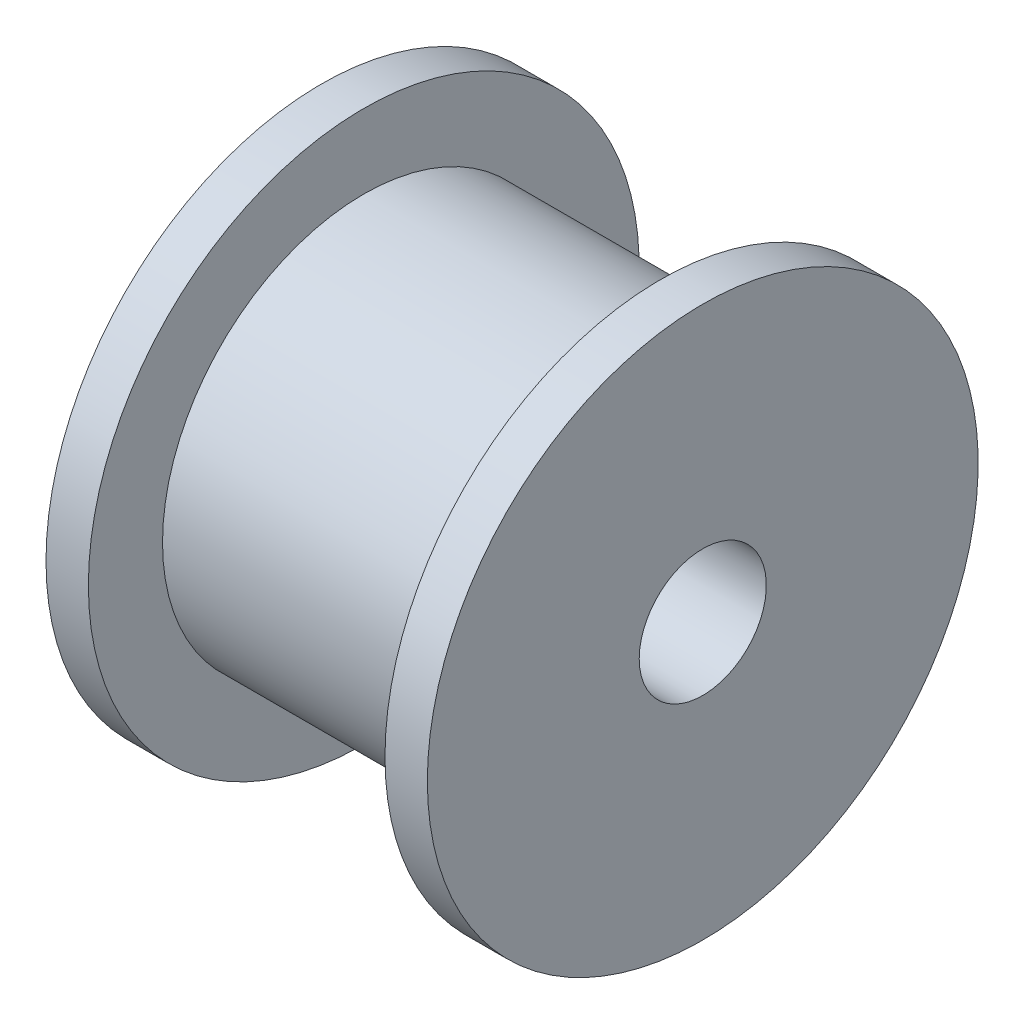
SolidWorks part; units mm, degrees
ref_plane "Спереди" through (0, 0, 0) normal (0, 0, 1) x (1, 0, 0)
ref_plane "Сверху" through (0, 0, 0) normal (0, 1, 0) x (1, 0, 0)
ref_plane "Справа" through (0, 0, 0) normal (1, 0, 0) x (0, 0, -1)
sketch "Эскиз1" plane through (0, 0, 0) normal (0, 0, 1) x (1, 0, 0)
  line L0 (0, 12.4245) -> (0, -12.3679) construction
  line L1 (-12.283, 0) -> (12.4528, 0) construction
  line L2 (0, 4.75) -> (3.5, 4.75)
  line L3 (3.5, 4.75) -> (3.5, 6.5)
  line L4 (3.5, 6.5) -> (4.5, 6.5)
  line L5 (4.5, 6.5) -> (4.5, 1.5)
  line L6 (4.5, 1.5) -> (0, 1.5)
  line L7 (0, 1.5) -> (-4.5, 1.5)
  line L8 (-4.5, 1.5) -> (-4.5, 6.5)
  line L9 (-4.5, 6.5) -> (-3.5, 6.5)
  line L10 (-3.5, 6.5) -> (-3.5, 4.75)
  line L11 (-3.5, 4.75) -> (0, 4.75)
  dimension "D1" = 1.5
  dimension "D2" = 6.5
  dimension "D3" = 7
  dimension "D4" = 1
  dimension "D5" = 4.75
  dimension "D6" = 9
revolve "Повернуть1" add sketch "Эскиз1" angle 360 about L1
